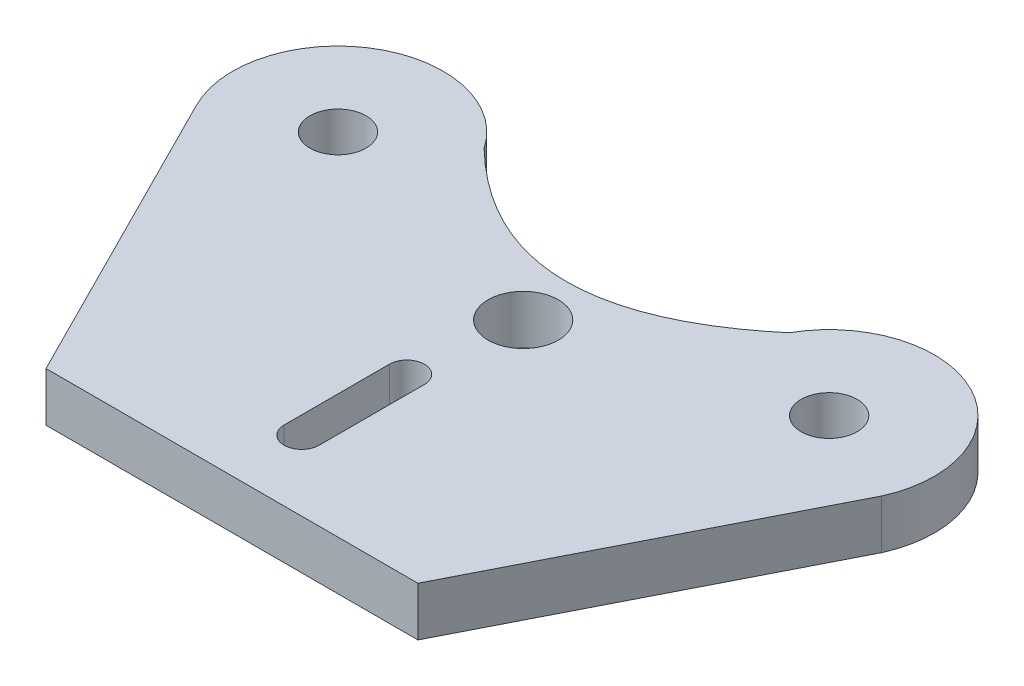
SolidWorks part; units mm, degrees
ref_plane "Front Plane" through (0, 0, 0) normal (0, 0, 1) x (1, 0, 0)
ref_plane "Top Plane" through (0, 0, 0) normal (0, 1, 0) x (1, 0, 0)
ref_plane "Right Plane" through (0, 0, 0) normal (1, 0, 0) x (0, 0, -1)
sketch "Sketch1" plane through (0, 0, 0) normal (0, 1, 0) x (1, 0, 0)
  line L0 (10.6627, -63.5) -> (77.9727, -63.5)
  line L1 (10.6627, -63.5) -> (-17.0126, -8.5717)
  line L2 (77.9727, -63.5) -> (106.2557, -7.8539)
  arc A0 (15.7946, 10.6506) -> (-17.0126, -8.5717) centre (0, 0) ccw
  arc A1 (105.4742, -9.3914) -> (72.3058, 9.356) centre (88.9, 0) ccw
  spline S0 degree 2 poles (15.7946, 10.6506) (42.7377, -15.5574) (72.3058, 9.356) knots 0 0 0 1 1 1
  point P4 (70.5143, 4.9867)
  point P7 (60.5746, -20.0763)
  point P11 (42.9573, -15.2453)
  point P12 (34.1255, -23.1889)
  point P14 (70.0241, -2.5687)
  point P16 (19.05, 0)
  point P17 (69.85, 0)
  point P18 (19.0266, -0.4579)
  point P19 (69.85, 0)
  point P20 (0, 0)
  point P21 (19.05, 0)
  point P22 (42.3027, -8.5717)
  point P23 (41.6247, -2.6862)
  dimension "D1" = 38.1
  dimension "D2" = 38.1
  dimension "D3" = 88.9
  dimension "D9" = 63.5
  dimension "D4" = 67.31
  dimension "D5" = 63.5
  dimension "D6" = 63.5
  dimension "D7" = 64.389
  dimension "D8" = 64.4333
extrude "Boss-Extrude1" add sketch "Sketch1" along normal blind 8.89 contours S0 A0 L1 L0 L2 A1
sketch "Sketch2" plane through (0, 8.89, 0) normal (0, 1, 0) x (1, 0, 0)
  line L0 (44.2312, -31.75) -> (44.2312, -50.8) construction
  line L1 (47.4062, -31.75) -> (47.4062, -50.8)
  line L2 (41.0562, -31.75) -> (41.0562, -50.8)
  line L3 (10.6627, -63.5) -> (77.9727, -63.5) construction
  arc A0 (47.4062, -31.75) -> (41.0562, -31.75) centre (44.2312, -31.75) ccw
  arc A1 (41.0562, -50.8) -> (47.4062, -50.8) centre (44.2312, -50.8) ccw
  point P2 (44.2312, -41.275)
  dimension "D1" = 19.05
  dimension "D2" = 12.7
  dimension "D3" = 6.35
extrude "Cut-Extrude1" cut sketch "Sketch2" against normal up to surface (8.89 mm away) up to face at (39.4891, 0, 15.189)
sketch "Sketch3" plane through (0, 8.89, 0) normal (0, 1, 0) x (1, 0, 0)
  circle A0 centre (0, 0) radius 5.08
  arc A1 (15.7946, 10.6506) -> (-17.0126, -8.5717) centre (0, 0) ccw construction
  dimension "D1" = 10.16
extrude "Cut-Extrude2" cut sketch "Sketch3" against normal up to surface (8.89 mm away) up to face at (44.2312, 0, 41.275)
sketch "Sketch4" plane through (0, 8.89, 0) normal (0, 1, 0) x (1, 0, 0)
  circle A0 centre (88.9, 0) radius 5.08
  arc A2 (106.2557, -7.8539) -> (72.3058, 9.356) centre (88.9, 0) ccw construction
  dimension "D1" = 10.16
  dimension "D2" = 0
extrude "Cut-Extrude3" cut sketch "Sketch4" against normal up to surface (8.89 mm away) up to face at (0, 0, 5.08)
sketch "Sketch5" plane through (0, 8.89, 0) normal (0, 1, 0) x (1, 0, 0)
  circle A0 centre (46.2308, -12.7) radius 6.35
  arc A1 (47.4062, -31.75) -> (41.0562, -31.75) centre (44.2312, -31.75) ccw construction
  dimension "D1" = 12.7
  dimension "D2" = 19.05
extrude "Cut-Extrude4" cut sketch "Sketch5" against normal up to surface (8.89 mm away) up to face at (88.9, 0, 5.08)
